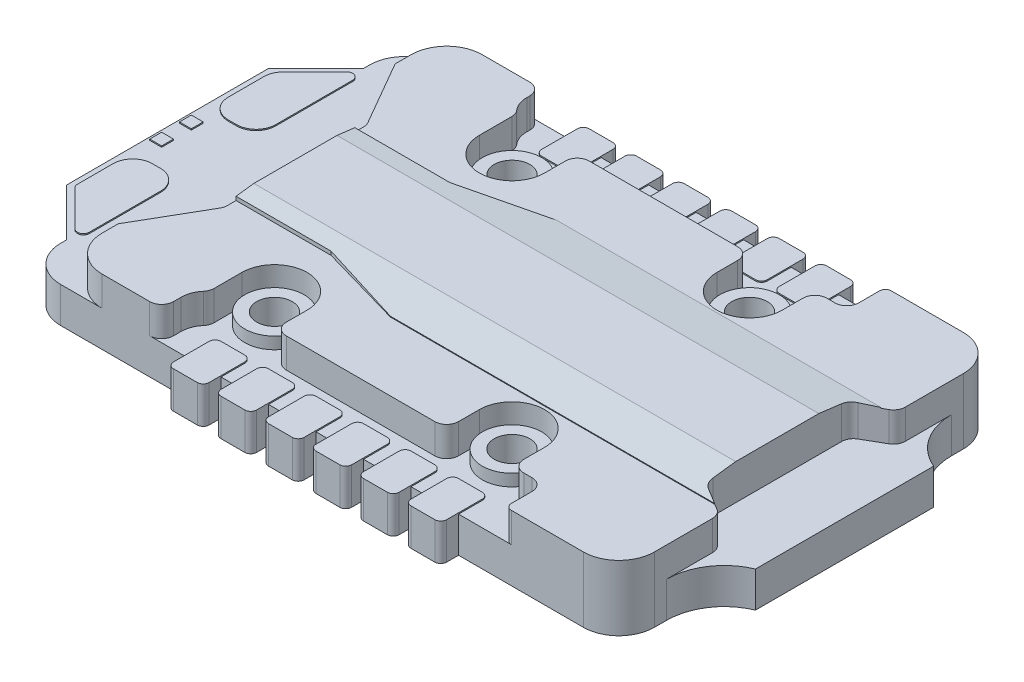
SolidWorks part; units mm, degrees
ref_plane "Front Plane" through (0, 0, 0) normal (0, 0, 1) x (1, 0, 0)
ref_plane "Top Plane" through (0, 0, 0) normal (0, 1, 0) x (1, 0, 0)
ref_plane "Right Plane" through (0, 0, 0) normal (1, 0, 0) x (0, 0, -1)
sketch "Sketch1" plane through (0, 0, 0) normal (0, 1, 0) x (1, 0, 0)
  line L1 (-22, 16) -> (22, 16)
  line L3 (-22, -16) -> (22, -16)
  line L4 (25, -12) -> (25, -16)
  line L8 (-29, 8.5) -> (-29, -8.5)
  line L9 (-29, -8.5) -> (-25, -12.5)
  line L10 (-25, -12.5) -> (-25, -13)
  line L11 (25, 13) -> (25, 12)
  line L15 (28, 7.5) -> (28, -7.5)
  line L16 (25, -13) -> (25, -12)
  line L17 (-25, 13) -> (-25, 12.5)
  line L18 (-29, 8.5) -> (-25, 12.5)
  arc A0 (25, 12) -> (28, 7.5) centre (29.875, 12) ccw
  arc A1 (25, -12) -> (28, -7.5) centre (29.875, -12) cw
  arc A2 (22, -16) -> (25, -13) centre (22, -13) ccw
  arc A3 (22, 16) -> (25, 13) centre (22, 13) cw
  arc A4 (-25, -13) -> (-22, -16) centre (-22, -13) ccw
  arc A5 (-22, 16) -> (-25, 13) centre (-22, 13) ccw
  point P21 (25, 16)
  point P26 (-25, 16)
  dimension "D13" = 3
  dimension "D14" = 3
  dimension "D2" = 32
  dimension "D3" = 16
  dimension "D4" = 25
  dimension "D5" = 17
  dimension "D6" = 45
  dimension "D7" = 8.5
  dimension "D8" = 15
  dimension "D9" = 3
  dimension "D10" = 7.5
  dimension "D11" = 4
  dimension "D12" = 4
  dimension "D15" = 44
  dimension "D16" = 44
  dimension "D17" = 4
  dimension "D18" = 4
extrude "Boss-Extrude1" add sketch "Sketch1" against normal blind 3 contours L1 A5 L17 L18 L8 L9 L10 A4 L3 A2 L4 A1 L15 A0 L11 A3
sketch "Sketch2" plane through (0, 0, 0) normal (0, 1, 0) x (1, 0, 0)
  circle A0 centre (-10, 10) radius 2.5
  circle A1 centre (10, 10) radius 2.5
  circle A2 centre (10, -10) radius 2.5
  circle A3 centre (-10, -10) radius 2.5
  dimension "D1" = 5
  dimension "D2" = 5
  dimension "D3" = 5
  dimension "D4" = 5
  dimension "D5" = 20
  dimension "D6" = 20
  dimension "D7" = 20
  dimension "D8" = 10
  dimension "D9" = 10
  dimension "D10" = 10
extrude "Boss-Extrude2" add sketch "Sketch2" along normal blind 1
sketch "Sketch3" plane through (0, 1, 0) normal (0, 1, 0) x (1, 0, 0)
  circle A0 centre (-10, 10) radius 1.5
  circle A1 centre (10, 10) radius 1.5
  circle A2 centre (10, -10) radius 1.5
  circle A3 centre (-10, -10) radius 1.5
  dimension "D1" = 3
  dimension "D2" = 3
  dimension "D3" = 3
  dimension "D4" = 3
extrude "Cut-Extrude1" cut sketch "Sketch3" against normal through all
sketch "Sketch4" plane through (0, 0, 0) normal (0, 1, 0) x (1, 0, 0)
  line L0 (-12.75, 10) -> (-12.75, 12.7348)
  line L1 (-7.25, 10) -> (-7.25, 11.75)
  line L2 (-6.25, 12.75) -> (6.25, 12.75)
  line L3 (7.25, 11.75) -> (7.25, 10)
  line L4 (12.75, 10) -> (12.75, 11.75)
  line L5 (13.75, 12.75) -> (14.4408, 12.75)
  line L6 (15.4408, 13.75) -> (15.4408, 15.5)
  line L7 (-22, 16) -> (22, 16) construction
  line L8 (15.9408, 16) -> (22, 16)
  line L9 (25, 13) -> (25, 8.1174)
  line L10 (24.5, 7.2513) -> (22.8326, 6.2887)
  line L11 (22.3326, 5.4226) -> (22.3326, -5.4226)
  line L12 (22.8326, -6.2887) -> (24.5, -7.2513)
  line L13 (25, -8.1174) -> (25, -13)
  line L14 (22, -16) -> (15.9408, -16)
  line L15 (-22, -16) -> (22, -16) construction
  line L16 (12.75, -10) -> (12.75, -11.75)
  line L17 (13.75, -12.75) -> (14.4408, -12.75)
  line L18 (15.4408, -13.75) -> (15.4408, -15.5)
  line L19 (7.25, -10) -> (7.25, -11.75)
  line L20 (6.25, -12.75) -> (-6.25, -12.75)
  line L21 (-7.25, -11.75) -> (-7.25, -10)
  line L22 (-13.5, 14.7425) -> (-13.5, 15)
  line L23 (-14.5, 16) -> (-18.5, 16)
  line L24 (-12.75, -10) -> (-12.75, -12.3367)
  line L25 (-13.5, -15) -> (-13.5, -14.3579)
  line L26 (-14.5, -16) -> (-18.5, -16)
  line L27 (-18.233, 5.7321) -> (-18.233, -5.7321)
  line L28 (-21.5, 13) -> (-21.5, 11.6587)
  line L29 (-18.3669, 6.2321) -> (-21.5, 11.6587)
  line L30 (-18.3669, -6.2321) -> (-21.5, -11.6587)
  line L31 (-21.5, -11.6587) -> (-21.5, -13)
  circle A0 centre (-10, 10) radius 2.75
  arc A1 (7.25, 10) -> (12.75, 10) centre (10, 10) ccw
  arc A2 (12.75, -10) -> (7.25, -10) centre (10, -10) ccw
  arc A3 (-7.25, -10) -> (-12.75, -10) centre (-10, -10) ccw
  arc A4 (25, 13) -> (22, 16) centre (22, 13) ccw
  arc A5 (22, -16) -> (25, -13) centre (22, -13) ccw
  arc A6 (-18.5, 16) -> (-21.5, 13) centre (-18.5, 13) ccw
  arc A7 (24.5, -7.2513) -> (25, -8.1174) centre (24, -8.1174) cw
  arc A8 (-13.5, 15) -> (-14.5, 16) centre (-14.5, 15) ccw
  arc A9 (-13.5, 14.7425) -> (-12.9949, 13.3905) centre (-11.4379, 14.7425) ccw
  arc A10 (-21.5, -13) -> (-18.5, -16) centre (-18.5, -13) ccw
  arc A11 (-13.5, -15) -> (-14.5, -16) centre (-14.5, -15) cw
  arc A12 (-13.5, -14.3579) -> (-12.9921, -12.989) centre (-11.4015, -14.3579) cw
  arc A13 (22.3326, -5.4226) -> (22.8326, -6.2887) centre (23.3326, -5.4226) ccw
  arc A14 (25, 8.1174) -> (24.5, 7.2513) centre (24, 8.1174) cw
  arc A15 (22.8326, 6.2887) -> (22.3326, 5.4226) centre (23.3326, 5.4226) ccw
  arc A16 (-18.233, -5.7321) -> (-18.3669, -6.2321) centre (-19.233, -5.7321) cw
  arc A17 (-18.233, 5.7321) -> (-18.3669, 6.2321) centre (-19.233, 5.7321) ccw
  arc A18 (-12.75, -12.3367) -> (-12.9921, -12.989) centre (-13.75, -12.3367) cw
  arc A19 (14.4408, -12.75) -> (15.4408, -13.75) centre (14.4408, -13.75) cw
  arc A20 (12.75, -11.75) -> (13.75, -12.75) centre (13.75, -11.75) ccw
  arc A21 (7.25, -11.75) -> (6.25, -12.75) centre (6.25, -11.75) cw
  arc A22 (-6.25, -12.75) -> (-7.25, -11.75) centre (-6.25, -11.75) cw
  arc A23 (14.4408, 12.75) -> (15.4408, 13.75) centre (14.4408, 13.75) ccw
  arc A24 (-12.75, 12.7348) -> (-12.9949, 13.3905) centre (-13.75, 12.7348) ccw
  arc A25 (12.75, 11.75) -> (13.75, 12.75) centre (13.75, 11.75) cw
  arc A26 (6.25, 12.75) -> (7.25, 11.75) centre (6.25, 11.75) cw
  arc A27 (-7.25, 11.75) -> (-6.25, 12.75) centre (-6.25, 11.75) cw
  arc A28 (15.9408, -16) -> (15.4408, -15.5) centre (15.9408, -15.5) cw
  arc A29 (15.4408, 15.5) -> (15.9408, 16) centre (15.9408, 15.5) cw
  point P32 (-13.5, 14.8712)
  point P57 (-13.5, 16)
  point P68 (-13.5, -16)
  point P71 (0, 0)
  point P78 (22.3326, -6)
  point P83 (22.3326, 6)
  point P86 (-18.233, -6)
  point P89 (-18.233, 6)
  point P110 (0, 0)
  point P113 (15.4408, -16)
  point P116 (15.4408, 16)
  line M25 (22, 16) -> (-22, 16)
  line M33 (-22, -16) -> (22, -16)
  arc M34 (22, -16) -> (25, -13) centre (22, -13) ccw
  line M35 (25, -13) -> (25, -12)
  dimension "D1" = 5.5
  dimension "D2" = 5.5
  dimension "D3" = 5.5
  dimension "D4" = 5.5
  dimension "D5" = 6
  dimension "D6" = 1
  dimension "D8" = 6
  dimension "D10" = 1
  dimension "D21" = 1
  dimension "D22" = 1
  dimension "D23" = 1
  dimension "D24" = 0.5
  dimension "D7" = 4
  dimension "D9" = 4
  dimension "D11" = 0.75
  dimension "D12" = 0.75
  dimension "D13" = 30
  dimension "D14" = 30
  dimension "D15" = 12
  dimension "D16" = 6
  dimension "D17" = 60
  dimension "D18" = 60
  dimension "D19" = 12
  dimension "D20" = 6
extrude "Boss-Extrude3" add sketch "Sketch4" along normal blind 2.5 contours A29 L6 A23 L5 A25 L4 A1 L3 A26 L2 A27 L1 A0 L0 A24 A9 L22 A8 A6 L28 L29 A17 L27 A16 L30 L31 A10 A11 L25 A12 A18 L24 A3 L21 A22 L20 A21 L19 A2 L16 A20 L17 A19 L18 A28 L13 M25 M33 M34 M35
sketch "Sketch5" plane through (0, 2.5, 0) normal (0, 1, 0) x (1, 0, 0)
  line L0 (-18.233, 5) -> (-10.233, 5)
  line L1 (-18.233, 5.7321) -> (-18.233, -5.7321) construction
  line L2 (-10.233, 5) -> (-3.233, 7)
  line L3 (-3.233, 7) -> (24.0647, 7)
  line L4 (-18.233, 5) -> (-18.233, -5)
  line L5 (-18.233, -5) -> (-10.233, -5)
  line L6 (-10.233, -5) -> (-3.233, -7)
  line L7 (-3.233, -7) -> (24.0647, -7)
  line L9 (22.3326, 5.4226) -> (22.3326, -5.4226)
  line L10 (22.8326, -6.2887) -> (24.0647, -7)
  line L11 (22.8326, 6.2887) -> (24.0647, 7)
  arc A0 (22.3326, -5.4226) -> (22.8326, -6.2887) centre (23.3326, -5.4226) ccw
  arc A1 (22.8326, 6.2887) -> (22.3326, 5.4226) centre (23.3326, 5.4226) ccw
  dimension "D1" = 10
  dimension "D2" = 5
  dimension "D3" = 8
  dimension "D4" = 8
  dimension "D5" = 2
  dimension "D6" = 2
  dimension "D7" = 7
  dimension "D8" = 7
extrude "Boss-Extrude4" add sketch "Sketch5" along normal blind 0.5
sketch "Sketch6" plane through (-18.233, 0, 0) normal (-1, 0, 0) x (0, 0, 1)
  line L0 (-3.5, 3) -> (3.5, 3)
  line L1 (-5, 3) -> (5, 3) construction
  line L2 (3.5, 3) -> (7.5, 2.5)
  line L3 (6.2321, 2.5) -> (11.6587, 2.5) construction
  line L4 (-3.5, 3) -> (-7.5, 2.5)
  line L5 (-6.2321, 2.5) -> (-11.6587, 2.5) construction
  line L6 (-7.5, 2.5) -> (-7.5, 6.2252)
  line L7 (-7.5, 6.2252) -> (7.5, 6.2252)
  line L8 (7.5, 6.2252) -> (7.5, 2.5)
  dimension "D1" = 7
  dimension "D2" = 3.5
  dimension "D3" = 4
  dimension "D4" = 4
extrude "Cut-Extrude2" cut sketch "Sketch6" against normal through all both and the other way through all
sketch "Sketch7" plane through (0, 0, 0) normal (0, 1, 0) x (1, 0, 0)
  line L0 (-14.5, -16) -> (15.9408, -16) construction
  line L1 (-11, -13.5) -> (-9, -13.5)
  line L2 (-11.5, -14) -> (-11.5, -17)
  line L3 (-11, -17.5) -> (-9, -17.5)
  line L4 (-8.5, -14) -> (-8.5, -17)
  line L5 (-7, -13.5) -> (-5, -13.5)
  line L6 (-7.5, -14) -> (-7.5, -17)
  line L7 (-7, -17.5) -> (-5, -17.5)
  line L8 (-4.5, -14) -> (-4.5, -17)
  line L9 (-3, -13.5) -> (-1, -13.5)
  line L10 (-3.5, -14) -> (-3.5, -17)
  line L11 (-3, -17.5) -> (-1, -17.5)
  line L12 (-0.5, -14) -> (-0.5, -17)
  line L13 (1, -13.5) -> (3, -13.5)
  line L14 (0.5, -14) -> (0.5, -17)
  line L15 (1, -17.5) -> (3, -17.5)
  line L16 (3.5, -14) -> (3.5, -17)
  line L17 (5, -13.5) -> (7, -13.5)
  line L18 (4.5, -14) -> (4.5, -17)
  line L19 (5, -17.5) -> (7, -17.5)
  line L20 (7.5, -14) -> (7.5, -17)
  line L21 (9, -13.5) -> (11, -13.5)
  line L22 (8.5, -14) -> (8.5, -17)
  line L23 (9, -17.5) -> (11, -17.5)
  line L24 (11.5, -14) -> (11.5, -17)
  line L25 (-28.3536, -8.4393) -> (-26.5052, -10.2877)
  line L26 (-29, -8.5) -> (-25, -12.5) construction
  line L27 (6.25, -12.75) -> (-6.25, -12.75) construction
  line L28 (-11, 17.5) -> (-9, 17.5)
  line L29 (-11.5, 17) -> (-11.5, 14)
  line L30 (-11, 13.5) -> (-9, 13.5)
  line L31 (-8.5, 17) -> (-8.5, 14)
  line L32 (-7, 17.5) -> (-5, 17.5)
  line L33 (-7.5, 17) -> (-7.5, 14)
  line L34 (-7, 13.5) -> (-5, 13.5)
  line L35 (-4.5, 17) -> (-4.5, 14)
  line L36 (-3, 17.5) -> (-1, 17.5)
  line L37 (-3.5, 17) -> (-3.5, 14)
  line L38 (-3, 13.5) -> (-1, 13.5)
  line L39 (-0.5, 17) -> (-0.5, 14)
  line L40 (1, 17.5) -> (3, 17.5)
  line L41 (0.5, 17) -> (0.5, 14)
  line L42 (1, 13.5) -> (3, 13.5)
  line L43 (3.5, 17) -> (3.5, 14)
  line L44 (5, 17.5) -> (7, 17.5)
  line L45 (4.5, 17) -> (4.5, 14)
  line L46 (5, 13.5) -> (7, 13.5)
  line L47 (7.5, 17) -> (7.5, 14)
  line L48 (9, 17.5) -> (11, 17.5)
  line L49 (8.5, 17) -> (8.5, 14)
  line L50 (9, 13.5) -> (11, 13.5)
  line L51 (11.5, 17) -> (11.5, 14)
  line L52 (-14.5, 16) -> (15.9408, 16) construction
  line L53 (-6.25, 12.75) -> (6.25, 12.75) construction
  line L55 (-26.8484, 2.9572) -> (-26.1516, 2.9572)
  line L56 (-28.5, 4.6088) -> (-28.5, 7.6088)
  line L58 (-24.5, 4.6088) -> (-24.5, 8.3056)
  line L59 (-26.8484, -3.4342) -> (-26.1516, -3.4342)
  line L60 (-28.5, -5.0858) -> (-28.5, -8.0858)
  line L63 (-29, 8.5) -> (-29, -8.5) construction
  line L64 (-28.0163, 8.7766) -> (-25.3536, 11.4393)
  line L66 (-28.75, 1.75) -> (-27.75, 1.75)
  line L67 (-28.75, 1.75) -> (-28.75, 0.75)
  line L68 (-28.75, 0.75) -> (-27.75, 0.75)
  line L69 (-27.75, 1.75) -> (-27.75, 0.75)
  line L70 (-28.75, -0.75) -> (-27.75, -0.75)
  line L71 (-28.75, -0.75) -> (-28.75, -1.75)
  line L72 (-28.75, -1.75) -> (-27.75, -1.75)
  line L73 (-27.75, -0.75) -> (-27.75, -1.75)
  line L75 (-26.5052, -10.2877) -> (-25.3536, -11.4393)
  line L77 (-24.5, 11.0858) -> (-24.5, 8.3056)
  line L78 (-24.5, -5.0858) -> (-24.5, -11.0858)
  arc A0 (-3, -13.5) -> (-3.5, -14) centre (-3, -14) ccw
  arc A1 (-1, -13.5) -> (-0.5, -14) centre (-1, -14) cw
  arc A2 (1, -13.5) -> (0.5, -14) centre (1, -14) ccw
  arc A3 (3, -13.5) -> (3.5, -14) centre (3, -14) cw
  arc A4 (5, -13.5) -> (4.5, -14) centre (5, -14) ccw
  arc A5 (7, -13.5) -> (7.5, -14) centre (7, -14) cw
  arc A6 (9, -13.5) -> (8.5, -14) centre (9, -14) ccw
  arc A7 (11, -13.5) -> (11.5, -14) centre (11, -14) cw
  arc A8 (11, -17.5) -> (11.5, -17) centre (11, -17) ccw
  arc A9 (8.5, -17) -> (9, -17.5) centre (9, -17) ccw
  arc A10 (7, -17.5) -> (7.5, -17) centre (7, -17) ccw
  arc A11 (4.5, -17) -> (5, -17.5) centre (5, -17) ccw
  arc A12 (3, -17.5) -> (3.5, -17) centre (3, -17) ccw
  arc A13 (0.5, -17) -> (1, -17.5) centre (1, -17) ccw
  arc A14 (-1, -17.5) -> (-0.5, -17) centre (-1, -17) ccw
  arc A15 (-3.5, -17) -> (-3, -17.5) centre (-3, -17) ccw
  arc A16 (-7.5, -17) -> (-7, -17.5) centre (-7, -17) ccw
  arc A17 (-5, -17.5) -> (-4.5, -17) centre (-5, -17) ccw
  arc A18 (-5, -13.5) -> (-4.5, -14) centre (-5, -14) cw
  arc A19 (-7, -13.5) -> (-7.5, -14) centre (-7, -14) ccw
  arc A20 (-11.5, -17) -> (-11, -17.5) centre (-11, -17) ccw
  arc A21 (-9, -17.5) -> (-8.5, -17) centre (-9, -17) ccw
  arc A22 (-9, -13.5) -> (-8.5, -14) centre (-9, -14) cw
  arc A23 (-11, -13.5) -> (-11.5, -14) centre (-11, -14) ccw
  arc A24 (11, 13.5) -> (11.5, 14) centre (11, 14) ccw
  arc A25 (8.5, 14) -> (9, 13.5) centre (9, 14) ccw
  arc A26 (7, 13.5) -> (7.5, 14) centre (7, 14) ccw
  arc A27 (4.5, 14) -> (5, 13.5) centre (5, 14) ccw
  arc A28 (3, 13.5) -> (3.5, 14) centre (3, 14) ccw
  arc A29 (0.5, 14) -> (1, 13.5) centre (1, 14) ccw
  arc A30 (-1, 13.5) -> (-0.5, 14) centre (-1, 14) ccw
  arc A31 (-3.5, 14) -> (-3, 13.5) centre (-3, 14) ccw
  arc A32 (-5, 13.5) -> (-4.5, 14) centre (-5, 14) ccw
  arc A33 (-7.5, 14) -> (-7, 13.5) centre (-7, 14) ccw
  arc A34 (-9, 13.5) -> (-8.5, 14) centre (-9, 14) ccw
  arc A35 (-11.5, 14) -> (-11, 13.5) centre (-11, 14) ccw
  arc A36 (11, 17.5) -> (11.5, 17) centre (11, 17) cw
  arc A37 (9, 17.5) -> (8.5, 17) centre (9, 17) ccw
  arc A38 (7, 17.5) -> (7.5, 17) centre (7, 17) cw
  arc A39 (5, 17.5) -> (4.5, 17) centre (5, 17) ccw
  arc A40 (3, 17.5) -> (3.5, 17) centre (3, 17) cw
  arc A41 (1, 17.5) -> (0.5, 17) centre (1, 17) ccw
  arc A42 (-1, 17.5) -> (-0.5, 17) centre (-1, 17) cw
  arc A43 (-3, 17.5) -> (-3.5, 17) centre (-3, 17) ccw
  arc A44 (-5, 17.5) -> (-4.5, 17) centre (-5, 17) cw
  arc A45 (-7, 17.5) -> (-7.5, 17) centre (-7, 17) ccw
  arc A46 (-9, 17.5) -> (-8.5, 17) centre (-9, 17) cw
  arc A47 (-11, 17.5) -> (-11.5, 17) centre (-11, 17) ccw
  arc A48 (-28.3536, -8.4393) -> (-28.5, -8.0858) centre (-28, -8.0858) cw
  arc A51 (-26.1516, -3.4342) -> (-24.5, -5.0858) centre (-26.1516, -5.0858) cw
  arc A52 (-26.8484, -3.4342) -> (-28.5, -5.0858) centre (-26.8484, -5.0858) ccw
  arc A53 (-26.8484, 2.9572) -> (-28.5, 4.6088) centre (-26.8484, 4.6088) cw
  arc A54 (-26.1516, 2.9572) -> (-24.5, 4.6088) centre (-26.1516, 4.6088) ccw
  arc A57 (-28.0163, 8.7766) -> (-28.5, 7.6088) centre (-26.8484, 7.6088) ccw
  arc A58 (-25.3536, -11.4393) -> (-24.5, -11.0858) centre (-25, -11.0858) ccw
  arc A59 (-25.3536, 11.4393) -> (-24.5, 11.0858) centre (-25, 11.0858) cw
  point P28 (0, -12.75)
  point P57 (0, 12.75)
  point P60 (-3.5, -13.5)
  point P65 (0.5, -13.5)
  point P70 (4.5, -13.5)
  point P75 (8.5, -13.5)
  point P80 (11.5, -17.5)
  point P83 (8.5, -17.5)
  point P86 (7.5, -17.5)
  point P89 (4.5, -17.5)
  point P92 (3.5, -17.5)
  point P95 (0.5, -17.5)
  point P98 (-0.5, -17.5)
  point P101 (-3.5, -17.5)
  point P104 (-7.5, -17.5)
  point P107 (-4.5, -17.5)
  point P112 (-7.5, -13.5)
  point P115 (-11.5, -17.5)
  point P118 (-8.5, -17.5)
  point P123 (-11.5, -13.5)
  point P126 (11.5, 13.5)
  point P129 (8.5, 13.5)
  point P132 (7.5, 13.5)
  point P135 (4.5, 13.5)
  point P138 (3.5, 13.5)
  point P141 (0.5, 13.5)
  point P144 (-0.5, 13.5)
  point P147 (-3.5, 13.5)
  point P150 (-4.5, 13.5)
  point P153 (-7.5, 13.5)
  point P156 (-8.5, 13.5)
  point P159 (-11.5, 13.5)
  point P164 (8.5, 17.5)
  point P169 (4.5, 17.5)
  point P174 (0.5, 17.5)
  point P179 (-3.5, 17.5)
  point P184 (-7.5, 17.5)
  point P189 (-11.5, 17.5)
  point P201 (0, 0)
  point P210 (0, 0)
  point P216 (-24.5, -3.4342)
  point P219 (-28.5, -3.4342)
  point P222 (-28.5, 2.9572)
  point P225 (-24.5, 2.9572)
  point P241 (-29, 0)
  dimension "D40" = 0.5
  dimension "D49" = 0.5
  dimension "D43" = 0.5
  dimension "D1" = 4
  dimension "D2" = 3
  dimension "D3" = 4
  dimension "D4" = 3
  dimension "D5" = 4
  dimension "D6" = 3
  dimension "D7" = 4
  dimension "D8" = 3
  dimension "D9" = 4
  dimension "D10" = 3
  dimension "D11" = 4
  dimension "D12" = 3
  dimension "D13" = 1
  dimension "D14" = 1
  dimension "D15" = 1
  dimension "D16" = 1
  dimension "D17" = 1
  dimension "D18" = 1.5
  dimension "D19" = 1.5
  dimension "D20" = 0.5
  dimension "D21" = 4
  dimension "D22" = 3
  dimension "D23" = 4
  dimension "D24" = 3
  dimension "D25" = 4
  dimension "D26" = 3
  dimension "D27" = 4
  dimension "D28" = 3
  dimension "D29" = 4
  dimension "D30" = 3
  dimension "D31" = 4
  dimension "D32" = 3
  dimension "D33" = 1
  dimension "D34" = 1
  dimension "D35" = 1
  dimension "D36" = 1
  dimension "D37" = 1
  dimension "D38" = 1.5
  dimension "D39" = 0.5
  dimension "D41" = 4
  dimension "D42" = 4
  dimension "D45" = 0.5
  dimension "D46" = 0.5
  dimension "D47" = 0.5
  dimension "D50" = 1
  dimension "D51" = 1
  dimension "D52" = 1
  dimension "D53" = 1
  dimension "D54" = 0.75
  dimension "D55" = 0.75
  dimension "D56" = 0.25
  dimension "D57" = 0.25
  dimension "D58" = 3
  dimension "D59" = 3
extrude "Boss-Extrude5" add sketch "Sketch7" along normal blind 0.1 and the other way blind 3
